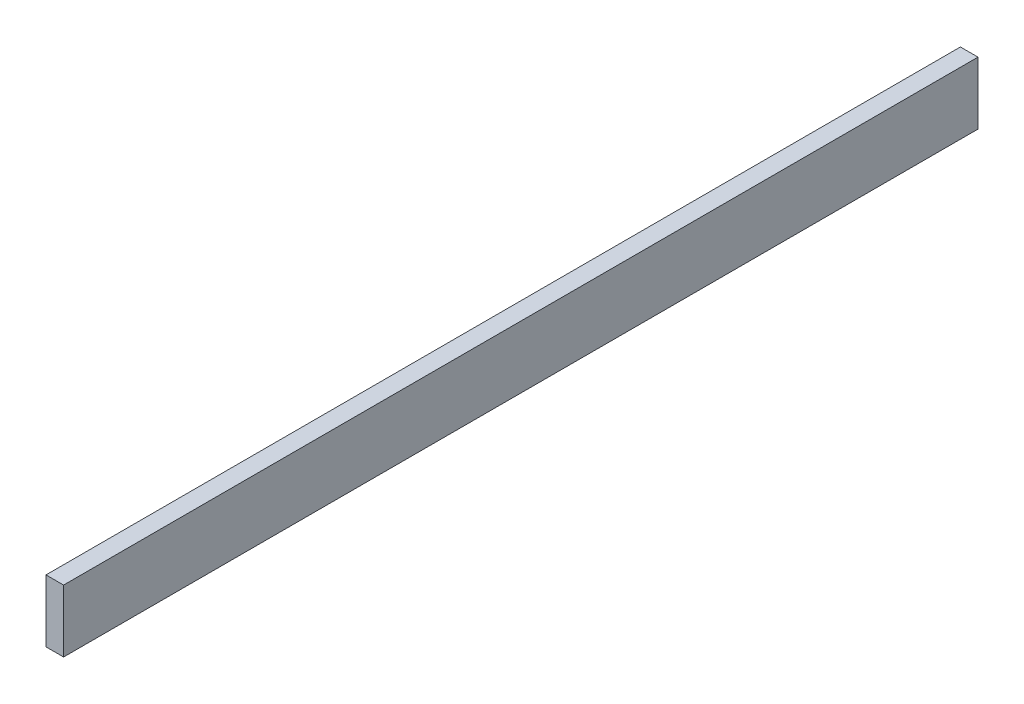
SolidWorks part; units mm, degrees
ref_plane "Front Plane" through (0, 0, 0) normal (0, 0, 1) x (1, 0, 0)
ref_plane "Top Plane" through (0, 0, 0) normal (0, 1, 0) x (1, 0, 0)
ref_plane "Right Plane" through (0, 0, 0) normal (1, 0, 0) x (0, 0, -1)
other "Configuration Table"
sketch "Sketch1" plane through (0, 0, 0) normal (0, 0, 1) x (1, 0, 0)
  line L1 (605.3, 14) -> (618, 14)
  line L2 (605.3, 14) -> (605.3, 59)
  line L3 (605.3, 59) -> (618, 59)
  line L4 (618, 14) -> (618, 59)
extrude "CEK_icecek_ray_ic_profil_sag_1" add sketch "Sketch1" against normal blind 660 separate body
